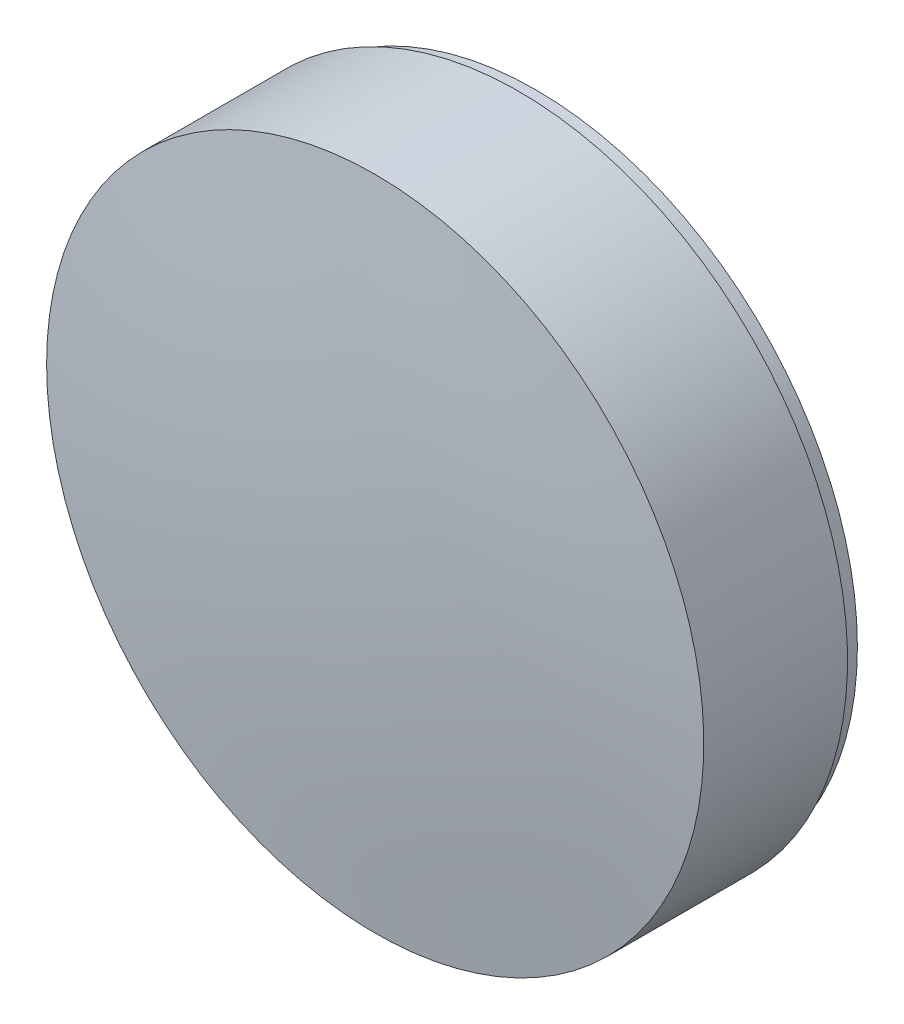
SolidWorks part; units mm, degrees
ref_plane "Front Plane" through (0, 0, 0) normal (0, 0, 1) x (1, 0, 0)
ref_plane "Top Plane" through (0, 0, 0) normal (0, 1, 0) x (1, 0, 0)
ref_plane "Right Plane" through (0, 0, 0) normal (1, 0, 0) x (0, 0, -1)
curve "Curve1"
  spline degree 3 poles (0, 0, 0) (0, 0.0167, 0) (0, 0.05, 0) (0, 0.1, -0.0002) (0, 0.15, -0.0004) (0, 0.2, -0.0007) (0, 0.25, -0.0012) (0, 0.3, -0.0017) (0, 0.35, -0.0023) (0, 0.4, -0.003) (0, 0.45, -0.0038) (0, 0.5, -0.0048) (0, 0.55, -0.0057) (0, 0.6, -0.0068) (0, 0.65, -0.008) (0, 0.7, -0.0093) (0, 0.75, -0.0107) (0, 0.8, -0.0121) (0, 0.85, -0.0137) (0, 0.9, -0.0154) (0, 0.95, -0.0171) (0, 1, -0.019) (0, 1.05, -0.0209) (0, 1.1, -0.0229) (0, 1.15, -0.0251) (0, 1.2, -0.0273) (0, 1.25, -0.0296) (0, 1.3, -0.032) (0, 1.35, -0.0345) (0, 1.4, -0.0371) (0, 1.45, -0.0397) (0, 1.5, -0.0425) (0, 1.55, -0.0454) (0, 1.6, -0.0483) (0, 1.65, -0.0513) (0, 1.7, -0.0545) (0, 1.75, -0.0577) (0, 1.8, -0.061) (0, 1.85, -0.0644) (0, 1.9, -0.0679) (0, 1.95, -0.0714) (0, 2, -0.0751) (0, 2.05, -0.0788) (0, 2.1, -0.0826) (0, 2.15, -0.0866) (0, 2.2, -0.0905) (0, 2.25, -0.0946) (0, 2.3, -0.0988) (0, 2.35, -0.103) (0, 2.4, -0.1073) (0, 2.45, -0.1117) (0, 2.5, -0.1162) (0, 2.55, -0.1208) (0, 2.6, -0.1254) (0, 2.65, -0.1301) (0, 2.7, -0.1349) (0, 2.75, -0.1398) (0, 2.8, -0.1447) (0, 2.85, -0.1497) (0, 2.9, -0.1547) (0, 2.95, -0.1599) (0, 3, -0.1651) (0, 3.05, -0.1703) (0, 3.1, -0.1756) (0, 3.15, -0.181) (0, 3.2, -0.1864) (0, 3.25, -0.1919) (0, 3.3, -0.1974) (0, 3.35, -0.203) (0, 3.4, -0.2087) (0, 3.45, -0.2143) (0, 3.5, -0.2201) (0, 3.55, -0.2258) (0, 3.6, -0.2316) (0, 3.65, -0.2374) (0, 3.7, -0.2433) (0, 3.75, -0.2492) (0, 3.8, -0.2551) (0, 3.85, -0.261) (0, 3.9, -0.267) (0, 3.95, -0.2729) (0, 4, -0.2789) (0, 4.05, -0.2849) (0, 4.1, -0.2909) (0, 4.15, -0.2969) (0, 4.2, -0.3028) (0, 4.25, -0.3088) (0, 4.3, -0.3148) (0, 4.35, -0.3208) (0, 4.4, -0.3268) (0, 4.45, -0.3327) (0, 4.5, -0.3386) (0, 4.55, -0.3446) (0, 4.6, -0.3505) (0, 4.6333, -0.3544) (0, 4.65, -0.3564) knots 0 0 0 0 0.010713 0.021427 0.032141 0.042854 0.053568 0.064282 0.074997 0.085711 0.096426 0.107141 0.117857 0.128573 0.139289 0.150006 0.160724 0.171442 0.182161 0.19288 0.2036 0.214321 0.225043 0.235765 0.246488 0.257212 0.267937 0.278663 0.28939 0.300117 0.310846 0.321576 0.332307 0.343039 0.353772 0.364507 0.375242 0.385979 0.396717 0.407457 0.418198 0.42894 0.439683 0.450428 0.461174 0.471922 0.482671 0.493421 0.504173 0.514927 0.525681 0.536438 0.547196 0.557955 0.568716 0.579478 0.590242 0.601007 0.611774 0.622543 0.633312 0.644083 0.654856 0.665629 0.676405 0.687181 0.697959 0.708738 0.719518 0.730299 0.741081 0.751865 0.762649 0.773434 0.78422 0.795007 0.805794 0.816582 0.827371 0.83816 0.848949 0.859739 0.870529 0.881319 0.892109 0.902899 0.913689 0.924479 0.935269 0.946058 0.956847 0.967636 0.978425 0.989213 1 1 1 1
sketch "Sketch1" plane through (0, 0, 0) normal (1, 0, 0) x (0, 0, -1)
  line L0 (0, 0) -> (2.99, 0)
  line L1 (2.39, 4.65) -> (0.3564, 4.65)
  line L3 (0.3268, 4.4) -> (2.6533, 4.4) construction
  line L4 (3.3646, 0) -> (-6.4067, 0) construction
  line L5 (2.39, 4.65) -> (2.39, 4.55)
  line L6 (2.39, 4.55) -> (2.6298, 4.55)
  arc A0 (2.99, 0) -> (2.6298, 4.55) centre (-25.9273, 0) ccw
  spline S0 degree 3 poles (-2999.7724, -23.2258) (5.4642, -18.2517) (-0.0258, -9.0804) (0.0002, 0.1) (0.0004, 0.15) (0.0007, 0.2) (0.0012, 0.25) (0.0017, 0.3) (0.0023, 0.35) (0.003, 0.4) (0.0038, 0.45) (0.0048, 0.5) (0.0057, 0.55) (0.0068, 0.6) (0.008, 0.65) (0.0093, 0.7) (0.0107, 0.75) (0.0121, 0.8) (0.0137, 0.85) (0.0154, 0.9) (0.0171, 0.95) (0.019, 1) (0.0209, 1.05) (0.0229, 1.1) (0.0251, 1.15) (0.0273, 1.2) (0.0296, 1.25) (0.032, 1.3) (0.0345, 1.35) (0.0371, 1.4) (0.0397, 1.45) (0.0425, 1.5) (0.0454, 1.55) (0.0483, 1.6) (0.0513, 1.65) (0.0545, 1.7) (0.0577, 1.75) (0.061, 1.8) (0.0644, 1.85) (0.0679, 1.9) (0.0714, 1.95) (0.0751, 2) (0.0788, 2.05) (0.0826, 2.1) (0.0866, 2.15) (0.0905, 2.2) (0.0946, 2.25) (0.0988, 2.3) (0.103, 2.35) (0.1073, 2.4) (0.1117, 2.45) (0.1162, 2.5) (0.1208, 2.55) (0.1254, 2.6) (0.1301, 2.65) (0.1349, 2.7) (0.1398, 2.75) (0.1447, 2.8) (0.1497, 2.85) (0.1547, 2.9) (0.1599, 2.95) (0.1651, 3) (0.1703, 3.05) (0.1756, 3.1) (0.181, 3.15) (0.1864, 3.2) (0.1919, 3.25) (0.1974, 3.3) (0.203, 3.35) (0.2087, 3.4) (0.2143, 3.45) (0.2201, 3.5) (0.2258, 3.55) (0.2316, 3.6) (0.2374, 3.65) (0.2433, 3.7) (0.2492, 3.75) (0.2551, 3.8) (0.261, 3.85) (0.267, 3.9) (0.2729, 3.95) (0.2789, 4) (0.2849, 4.05) (0.2909, 4.1) (0.2969, 4.15) (0.3028, 4.2) (0.3088, 4.25) (0.3148, 4.3) (0.3208, 4.35) (0.3268, 4.4) (0.3327, 4.45) (0.3386, 4.5) (0.3446, 4.55) (1.8815, 17.548) (-0.4374, 30.9832) (2983.8403, -307.3082) knots -5.869106 -5.869106 -5.869106 -5.869106 0.010713 0.021427 0.032141 0.042854 0.053568 0.064282 0.074997 0.085711 0.096426 0.107141 0.117857 0.128573 0.139289 0.150006 0.160724 0.171442 0.182161 0.19288 0.2036 0.214321 0.225043 0.235765 0.246488 0.257212 0.267937 0.278663 0.28939 0.300117 0.310846 0.321576 0.332307 0.343039 0.353772 0.364507 0.375242 0.385979 0.396717 0.407457 0.418198 0.42894 0.439683 0.450428 0.461174 0.471922 0.482671 0.493421 0.504173 0.514927 0.525681 0.536438 0.547196 0.557955 0.568716 0.579478 0.590242 0.601007 0.611774 0.622543 0.633312 0.644083 0.654856 0.665629 0.676405 0.687181 0.697959 0.708738 0.719518 0.730299 0.741081 0.751865 0.762649 0.773434 0.78422 0.795007 0.805794 0.816582 0.827371 0.83816 0.848949 0.859739 0.870529 0.881319 0.892109 0.902899 0.913689 0.924479 0.935269 0.946058 0.956847 0.967636 0.978425 0.989213 9.38109 9.38109 9.38109 9.38109 only from (0, 0) to (0.3564, 4.65) construction
  spline S1 degree 3 poles (0, 0) (0, 0.0167) (0, 0.05) (0.0002, 0.1) (0.0004, 0.15) (0.0007, 0.2) (0.0012, 0.25) (0.0017, 0.3) (0.0023, 0.35) (0.003, 0.4) (0.0038, 0.45) (0.0048, 0.5) (0.0057, 0.55) (0.0068, 0.6) (0.008, 0.65) (0.0093, 0.7) (0.0107, 0.75) (0.0121, 0.8) (0.0137, 0.85) (0.0154, 0.9) (0.0171, 0.95) (0.019, 1) (0.0209, 1.05) (0.0229, 1.1) (0.0251, 1.15) (0.0273, 1.2) (0.0296, 1.25) (0.032, 1.3) (0.0345, 1.35) (0.0371, 1.4) (0.0397, 1.45) (0.0425, 1.5) (0.0454, 1.55) (0.0483, 1.6) (0.0513, 1.65) (0.0545, 1.7) (0.0577, 1.75) (0.061, 1.8) (0.0644, 1.85) (0.0679, 1.9) (0.0714, 1.95) (0.0751, 2) (0.0788, 2.05) (0.0826, 2.1) (0.0866, 2.15) (0.0905, 2.2) (0.0946, 2.25) (0.0988, 2.3) (0.103, 2.35) (0.1073, 2.4) (0.1117, 2.45) (0.1162, 2.5) (0.1208, 2.55) (0.1254, 2.6) (0.1301, 2.65) (0.1349, 2.7) (0.1398, 2.75) (0.1447, 2.8) (0.1497, 2.85) (0.1547, 2.9) (0.1599, 2.95) (0.1651, 3) (0.1703, 3.05) (0.1756, 3.1) (0.181, 3.15) (0.1864, 3.2) (0.1919, 3.25) (0.1974, 3.3) (0.203, 3.35) (0.2087, 3.4) (0.2143, 3.45) (0.2201, 3.5) (0.2258, 3.55) (0.2316, 3.6) (0.2374, 3.65) (0.2433, 3.7) (0.2492, 3.75) (0.2551, 3.8) (0.261, 3.85) (0.267, 3.9) (0.2729, 3.95) (0.2789, 4) (0.2849, 4.05) (0.2909, 4.1) (0.2969, 4.15) (0.3028, 4.2) (0.3088, 4.25) (0.3148, 4.3) (0.3208, 4.35) (0.3268, 4.4) (0.3327, 4.45) (0.3386, 4.5) (0.3446, 4.55) (0.3505, 4.6) (0.3544, 4.6333) (0.3564, 4.65) knots 0 0 0 0 0.010713 0.021427 0.032141 0.042854 0.053568 0.064282 0.074997 0.085711 0.096426 0.107141 0.117857 0.128573 0.139289 0.150006 0.160724 0.171442 0.182161 0.19288 0.2036 0.214321 0.225043 0.235765 0.246488 0.257212 0.267937 0.278663 0.28939 0.300117 0.310846 0.321576 0.332307 0.343039 0.353772 0.364507 0.375242 0.385979 0.396717 0.407457 0.418198 0.42894 0.439683 0.450428 0.461174 0.471922 0.482671 0.493421 0.504173 0.514927 0.525681 0.536438 0.547196 0.557955 0.568716 0.579478 0.590242 0.601007 0.611774 0.622543 0.633312 0.644083 0.654856 0.665629 0.676405 0.687181 0.697959 0.708738 0.719518 0.730299 0.741081 0.751865 0.762649 0.773434 0.78422 0.795007 0.805794 0.816582 0.827371 0.83816 0.848949 0.859739 0.870529 0.881319 0.892109 0.902899 0.913689 0.924479 0.935269 0.946058 0.956847 0.967636 0.978425 0.989213 1 1 1 1
  point P4 (-0.3602, 4.55)
  dimension "D2" = 28.9173
  dimension "D3" = 2.99
  dimension "D8" = 9.1
  dimension "D1" = 0.6
  dimension "D5" = 9.3
  dimension "D6" = 8.8
revolve "Revolve1" add sketch "Sketch1" angle 360 about L4
ref_plane "Plane1" through (0, 0, 0.376) normal (0, 0, 1) x (1, 0, 0)
sketch "Sketch2" plane through (0, 0, -2.39) normal (0, 0, 1) x (1, 0, 0)
  line L0 (0, 0) -> (7.3914, 0) construction
  line L1 (4.0914, 1.5819) -> (7.3914, 1)
  line L2 (4.3914, 1.529) -> (4.3914, -1.529) construction
  line L3 (4.0914, -1.5819) -> (7.3914, -1)
  line L4 (7.3914, 1) -> (7.3914, -1)
  line L8 (4.0914, 1.5819) -> (4.0914, -1.5819)
  circle A0 centre (0, 0) radius 4.65 construction
  dimension "D1" = 20
  dimension "D2" = 3.3
  dimension "D3" = 2
  dimension "D5" = 0.3
extrude "Gate" [suppressed] add sketch "Sketch2" along normal blind 1.75 draft 2
fillet "Fillet2" [suppressed] radius 0.7874
